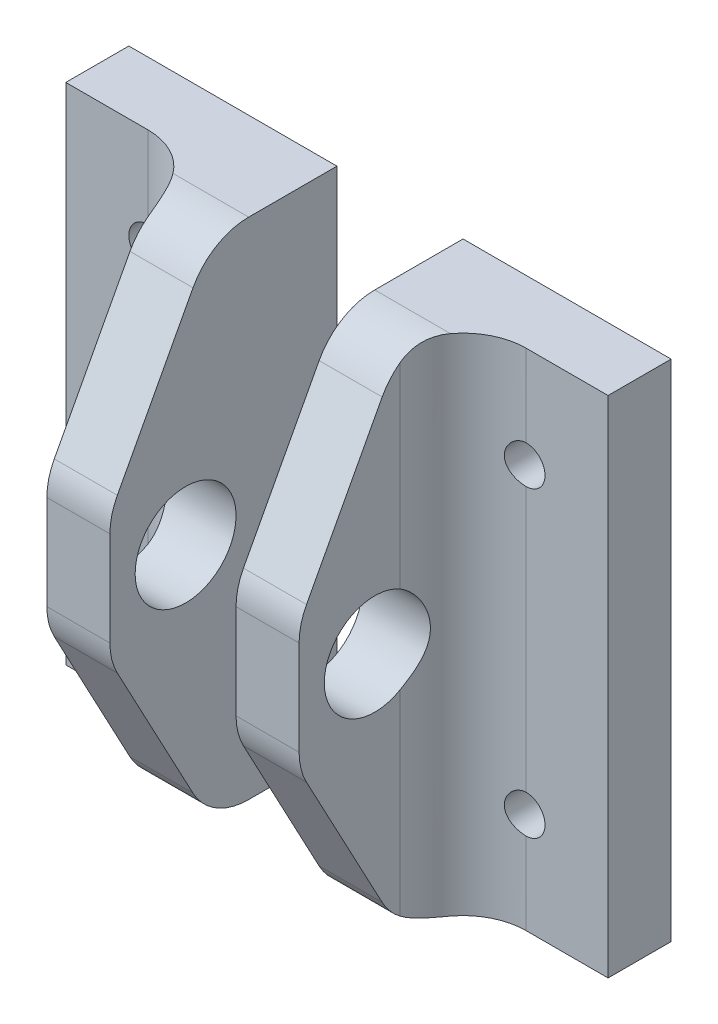
SolidWorks part; units mm, degrees
ref_plane "Front Plane" through (0, 0, 0) normal (0, 0, 1) x (1, 0, 0)
ref_plane "Top Plane" through (0, 0, 0) normal (0, 1, 0) x (1, 0, 0)
ref_plane "Right Plane" through (0, 0, 0) normal (1, 0, 0) x (0, 0, -1)
sketch "Sketch1" plane through (0, 0, 0) normal (0, 1, 0) x (1, 0, 0)
  line L0 (0, 0) -> (0, 22.4056) construction
  line L5 (-5, 18) -> (-5, 0)
  line L6 (-5, 0) -> (-10, 0)
  line L7 (-10, 0) -> (-10, 8)
  line L8 (-15, 13) -> (-21.5, 13)
  line L9 (-21.5, 13) -> (-21.5, 18)
  line L10 (-21.5, 18) -> (-5, 18)
  line L11 (21.5, 18) -> (5, 18)
  line L12 (21.5, 13) -> (21.5, 18)
  line L13 (15, 13) -> (21.5, 13)
  line L14 (10, 0) -> (10, 8)
  line L15 (5, 0) -> (10, 0)
  line L16 (5, 18) -> (5, 0)
  arc A0 (-10, 8) -> (-15, 13) centre (-15, 8) ccw
  arc A1 (10, 8) -> (15, 13) centre (15, 8) cw
  point P17 (-10, 13)
  point P20 (10, 13)
  dimension "D6" = 5
  dimension "D7" = 5
  dimension "D1" = 5
  dimension "D2" = 5
  dimension "D3" = 16.5
  dimension "D4" = 18
  dimension "D5" = 5
extrude "Boss-Extrude1" add sketch "Sketch1" along normal mid plane 40
sketch "Sketch2" plane through (10, 0, 0) normal (1, 0, 0) x (0, 0, -1)
  line L0 (0, 0) -> (10.468, 0) construction
  line L1 (0, 20) -> (0, -20) construction
  circle A0 centre (6, 0) radius 4
  dimension "D1" = 8
  dimension "D2" = 6
extrude "Cut-Extrude1" cut sketch "Sketch2" against normal through all both and the other way through all
sketch "Sketch3" plane through (0, 0, -18) normal (0, 0, -1) x (-1, 0, 0)
  line L0 (0, 0) -> (-28.0618, 0) construction
  line L1 (0, 0) -> (0, 31.3837) construction
  circle A0 centre (-15, -12) radius 1.5
  circle A1 centre (-15, 12) radius 1.5
  circle A2 centre (15, 12) radius 1.5
  circle A3 centre (15, -12) radius 1.5
  dimension "D1" = 3
  dimension "D3" = 30
  dimension "D2" = 24
extrude "Cut-Extrude2" cut sketch "Sketch3" against normal through all both and the other way through all
sketch "Sketch4" plane through (10, 0, 0) normal (1, 0, 0) x (0, 0, -1)
  line L0 (8, 20) -> (0, 5)
  line L1 (0, 20) -> (0, -20) construction
  line L2 (0, 0) -> (6, 0) construction
  line L3 (8, -20) -> (0, -5)
  line L4 (8, 20) -> (0, 20)
  line L5 (0, 20) -> (0, 5)
  line L6 (0, -5) -> (0, -20)
  line L7 (0, -20) -> (8, -20)
  dimension "D1" = 10
extrude "Cut-Extrude3" cut sketch "Sketch4" against normal through all both and the other way through all
fillet "Fillet2" radius 5 4 edges at (7.5, -20, -8) (7.5, -5, 0) (7.5, 5, 0) (7.5, 20, -8)
fillet "Fillet3" radius 5 4 edges at (-7.5, -20, -8) (-7.5, -5, 0) (-7.5, 5, 0) (-7.5, 20, -8)
